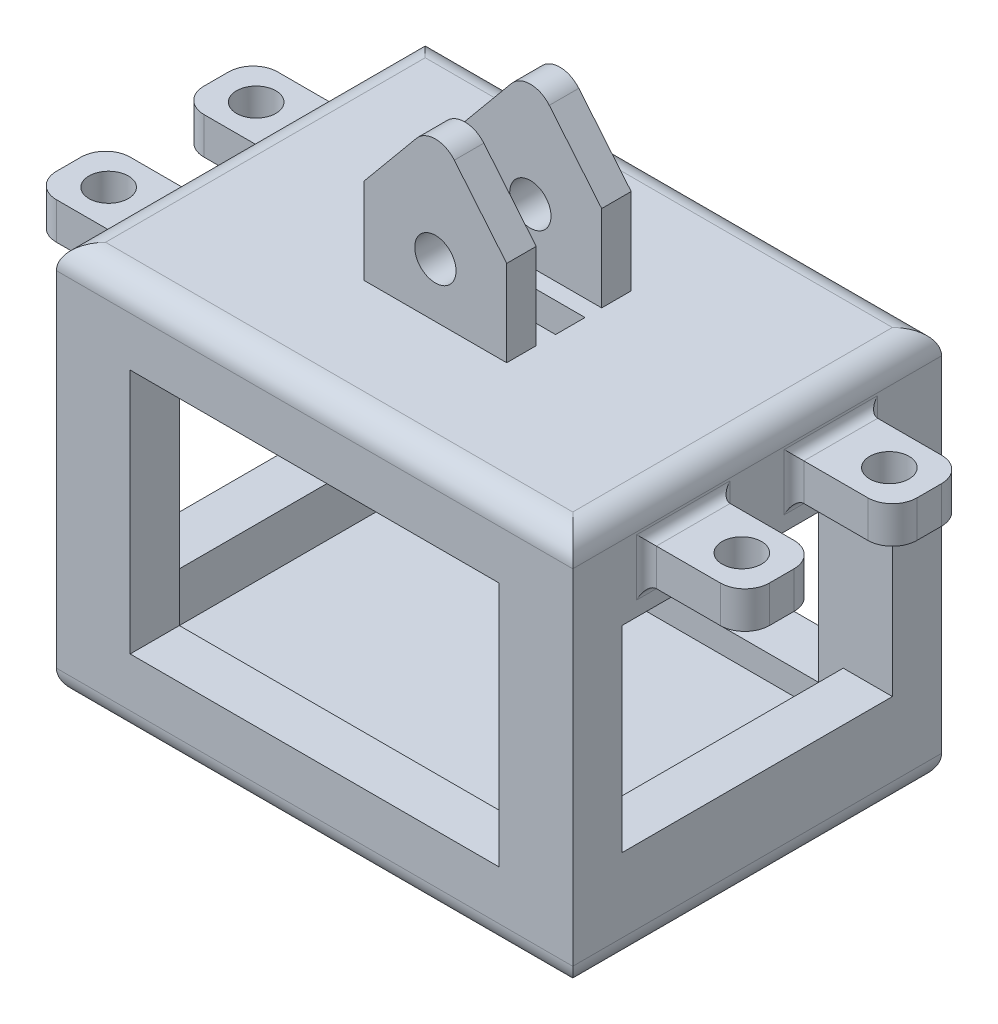
SolidWorks part; units mm, degrees
ref_plane "Front Plane" through (0, 0, 0) normal (0, 0, 1) x (1, 0, 0)
ref_plane "Top Plane" through (0, 0, 0) normal (0, 1, 0) x (1, 0, 0)
ref_plane "Right Plane" through (0, 0, 0) normal (1, 0, 0) x (0, 0, -1)
sketch "Sketch1" plane through (0, 0, 0) normal (0, 1, 0) x (1, 0, 0)
  line L1 (0, 0) -> (105, 0)
  line L2 (0, 0) -> (0, 75)
  line L3 (0, 75) -> (105, 75)
  line L4 (105, 0) -> (105, 75)
  dimension "D1" = 105
  dimension "D2" = 75
extrude "Boss-Extrude1" add sketch "Sketch1" along normal blind 80
shell "Shell1" thickness 10
sketch "Sketch2" plane through (0, 0, -65) normal (0, 0, 1) x (1, 0, 0)
  line L0 (0, 80) -> (0, 0) construction
  line L1 (0, 70) -> (10, 70)
  line L2 (0, 70) -> (0, 10)
  line L3 (0, 10) -> (10, 10)
  line L4 (10, 70) -> (10, 10)
  line L5 (0, 80) -> (105, 80) construction
  line L6 (0, 0) -> (105, 0) construction
  dimension "D1" = 10
  dimension "D2" = 10
  dimension "D3" = 10
extrude "Boss-Extrude2" add sketch "Sketch2" along normal blind 60
fillet "Fillet1" radius 5 8 edges at (105, 0, -37.5) (52.5, 0, -75) (0, 0, -37.5) (52.5, 0, 0) (52.5, 80, 0) (0, 80, -37.5) (52.5, 80, -75) (105, 80, -37.5)
sketch "Sketch3" plane through (0, 0, 0) normal (0, 0, 1) x (1, 0, 0)
  line L0 (100, 0) -> (5, 0) construction
  line L1 (15, 65) -> (90, 65)
  line L2 (15, 65) -> (15, 15)
  line L3 (15, 15) -> (90, 15)
  line L4 (90, 65) -> (90, 15)
  line L5 (5, 80) -> (100, 80) construction
  line L6 (105, 75) -> (105, 5) construction
  line L7 (0, 75) -> (0, 5) construction
  dimension "D1" = 15
  dimension "D2" = 15
  dimension "D3" = 15
  dimension "D4" = 15
extrude "Cut-Extrude1" cut sketch "Sketch3" against normal through all
sketch "Sketch4" plane through (0, 0, 0) normal (-1, 0, 0) x (0, 0, 1)
  line L0 (-75, 75) -> (-75, 5) construction
  line L1 (-65, 60) -> (-10, 60)
  line L2 (-65, 60) -> (-65, 20)
  line L3 (-65, 20) -> (-10, 20)
  line L4 (-10, 60) -> (-10, 20)
  line L5 (0, 75) -> (0, 5) construction
  line L6 (-70, 80) -> (-5, 80) construction
  line L7 (-5, 0) -> (-70, 0) construction
  dimension "D1" = 10
  dimension "D2" = 10
  dimension "D3" = 20
  dimension "D4" = 20
extrude "Cut-Extrude2" cut sketch "Sketch4" against normal through all
sketch "Sketch5" plane through (105, 0, 0) normal (1, 0, 0) x (0, 0, -1)
  line L0 (10, 60) -> (65, 60) construction
  line L1 (15, 72.5) -> (30, 72.5)
  line L2 (15, 72.5) -> (15, 65)
  line L3 (15, 65) -> (30, 65)
  line L4 (30, 72.5) -> (30, 65)
  line L5 (0, 75) -> (0, 5) construction
  dimension "D1" = 5
  dimension "D2" = 15
  dimension "D3" = 15
  dimension "D4" = 7.5
extrude "Boss-Extrude3" add sketch "Sketch5" along normal blind 20
sketch "Sketch6" plane through (0, 72.5, 0) normal (0, 1, 0) x (1, 0, 0)
  line L1 (105, 30) -> (120, 30)
  line L2 (105, 30) -> (105, 15)
  line L3 (105, 15) -> (120, 15)
  line L4 (125, 25) -> (125, 20)
  arc A0 (125, 25) -> (120, 30) centre (120, 25) ccw
  arc A1 (120, 15) -> (125, 20) centre (120, 20) ccw
  circle A2 centre (116.8775, 22.5) radius 4
  point P10 (125, 15)
  point P13 (0, 0)
  point P14 (0, 0)
  point P15 (105, 22.5)
  line M8 (105, 15) -> (125, 15)
  line M9 (125, 15) -> (125, 30)
  line M10 (125, 30) -> (105, 30)
  dimension "D1" = 5
  dimension "D2" = 5
  dimension "D3" = 8
extrude "Cut-Extrude3" cut sketch "Sketch6" against normal through all contours A0 M9 M10 | A2 | A1 M8 M9
ref_plane "Mid-Plane" through (0, 0, -37.5) normal (0, 0, 1) x (1, 0, 0)
ref_plane "Mid-Plane2" through (52.5, 0, 0) normal (1, 0, 0) x (0, 0, -1)
mirror "Mirror1" about plane through (52.5, 0, 0) normal (1, 0, 0) of "Cut-Extrude3", "Boss-Extrude3"
mirror "Mirror2" about plane through (0, 0, -37.5) normal (0, 0, 1) of "Mirror1", "Boss-Extrude3", "Cut-Extrude3"
fillet "Fillet3" radius 2 16 edges at (105, 65, -22.5) (105, 68.75, -30) (105, 72.5, -22.5) (105, 68.75, -15) (105, 65, -52.5) (105, 68.75, -45) (105, 68.75, -60) (105, 72.5, -52.5) (0, 68.75, -30) (0, 65, -22.5) (0, 68.75, -15) (0, 72.5, -22.5) (0, 68.75, -45) (0, 65, -52.5) (0, 68.75, -60) (0, 72.5, -52.5)
sketch "Sketch7" plane through (0, 80, 0) normal (0, 1, 0) x (1, 0, 0)
  line L0 (0, 0) -> (0, 75) construction
  line L1 (38, 40.5) -> (67, 40.5)
  line L2 (38, 40.5) -> (38, 34.5)
  line L3 (38, 34.5) -> (67, 34.5)
  line L4 (67, 40.5) -> (67, 34.5)
  line L5 (105, 75) -> (105, 0) construction
  line L6 (105, 0) -> (0, 0) construction
  dimension "D1" = 6
  dimension "D2" = 38
  dimension "D3" = 38
  dimension "D4" = 34.5
extrude "Cut-Extrude4" cut sketch "Sketch7" against normal blind 15
sketch "Sketch8" plane through (0, 80, 0) normal (0, 1, 0) x (1, 0, 0)
  line L0 (67, 34.5) -> (67, 40.5) construction
  line L1 (38, 49.8772) -> (67, 49.8772)
  line L2 (38, 49.8772) -> (38, 43.8772)
  line L3 (38, 43.8772) -> (67, 43.8772)
  line L4 (67, 49.8772) -> (67, 43.8772)
  line L5 (38, 30.5633) -> (67, 30.5633)
  line L6 (38, 30.5633) -> (38, 24.5633)
  line L7 (38, 24.5633) -> (67, 24.5633)
  line L8 (67, 30.5633) -> (67, 24.5633)
  line L9 (38, 40.5) -> (38, 34.5) construction
  dimension "D1" = 6
extrude "Boss-Extrude4" add sketch "Sketch8" along normal blind 35
sketch "Sketch9" plane through (0, 0, -24.5633) normal (0, 0, 1) x (1, 0, 0)
  line L0 (38, 80) -> (38, 115)
  line L1 (38, 115) -> (67, 115)
  line L2 (67, 115) -> (67, 80)
  line L3 (38, 80) -> (67, 80) construction
  line L4 (38, 97.5) -> (48.6499, 110.3533)
  line L5 (56.3501, 110.3533) -> (67, 97.5)
  circle A0 centre (52.5, 91) radius 4.2
  arc A1 (56.3501, 110.3533) -> (48.6499, 110.3533) centre (52.5, 107.1632) ccw
  point P17 (52.5, 115)
  line M4 (67, 115) -> (38, 115)
  line M5 (38, 115) -> (38, 80)
  dimension "D1" = 11
  dimension "D3" = 8.4
  dimension "D4" = 5
  dimension "D2" = 14.5
extrude "Cut-Extrude5" cut sketch "Sketch9" against normal blind 35 contours A1 L5 L2 L4 M4 M5 | A0
